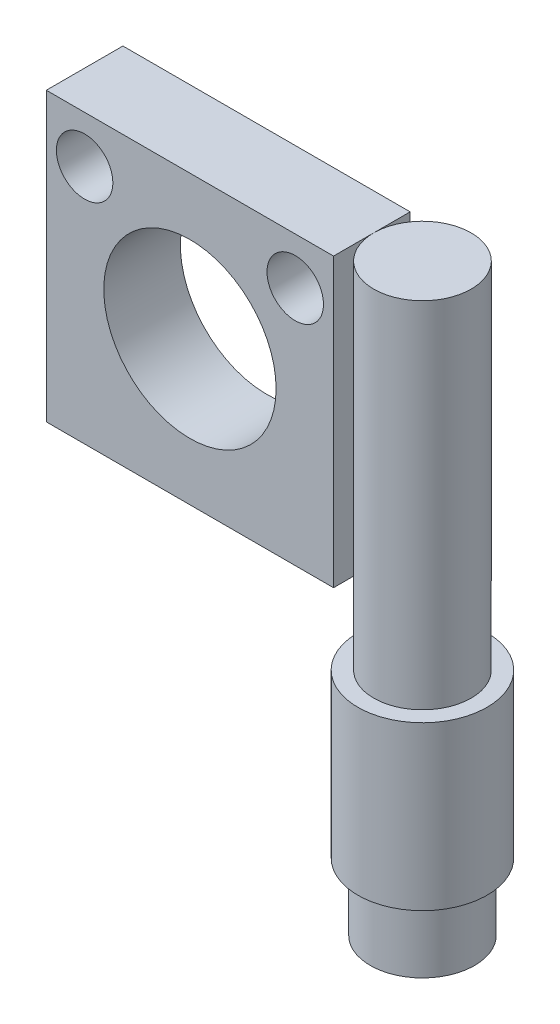
SolidWorks part; units mm, degrees
ref_plane "Alzado" through (0, 0, 0) normal (0, 0, 1) x (1, 0, 0)
ref_plane "Planta" through (0, 0, 0) normal (0, 1, 0) x (1, 0, 0)
ref_plane "Vista lateral" through (0, 0, 0) normal (1, 0, 0) x (0, 0, -1)
sketch "Croquis1" plane through (0, 0, 0) normal (0, 0, 1) x (1, 0, 0)
  line L1 (-15, 15) -> (15, 15)
  line L2 (-15, 15) -> (-15, -15)
  line L3 (-15, -15) -> (15, -15)
  line L4 (15, 15) -> (15, -15)
  line L5 (-15, 15) -> (15, -15) construction
  line L6 (-15, -15) -> (15, 15) construction
  circle A0 centre (0, 0) radius 9
  circle A1 centre (-11, 10.1) radius 2.95
  circle A3 centre (11, 10.1) radius 2.95
  point P0 (0, 0)
  dimension "D1" = 30
  dimension "30" = 30
extrude "Saliente-Extruir2" add sketch "Croquis1" along normal blind 8
sketch "Croquis3" plane through (0, 15, 0) normal (0, 1, 0) x (1, 0, 0)
  circle A0 centre (20.0879, -3.8024) radius 5.0879
extrude "Saliente-Extruir3" add sketch "Croquis3" against normal blind 37 separate body
sketch "Croquis4" plane through (0, -22, 0) normal (0, -1, 0) x (1, 0, 0)
  circle A0 centre (20.0879, 3.8024) radius 6.7448
extrude "Saliente-Extruir4" add sketch "Croquis4" along normal blind 17
sketch "Croquis5" plane through (0, -39, 0) normal (0, -1, 0) x (1, 0, 0)
  circle A0 centre (20.0879, 3.8024) radius 5.4517
extrude "Saliente-Extruir5" add sketch "Croquis5" along normal blind 7
